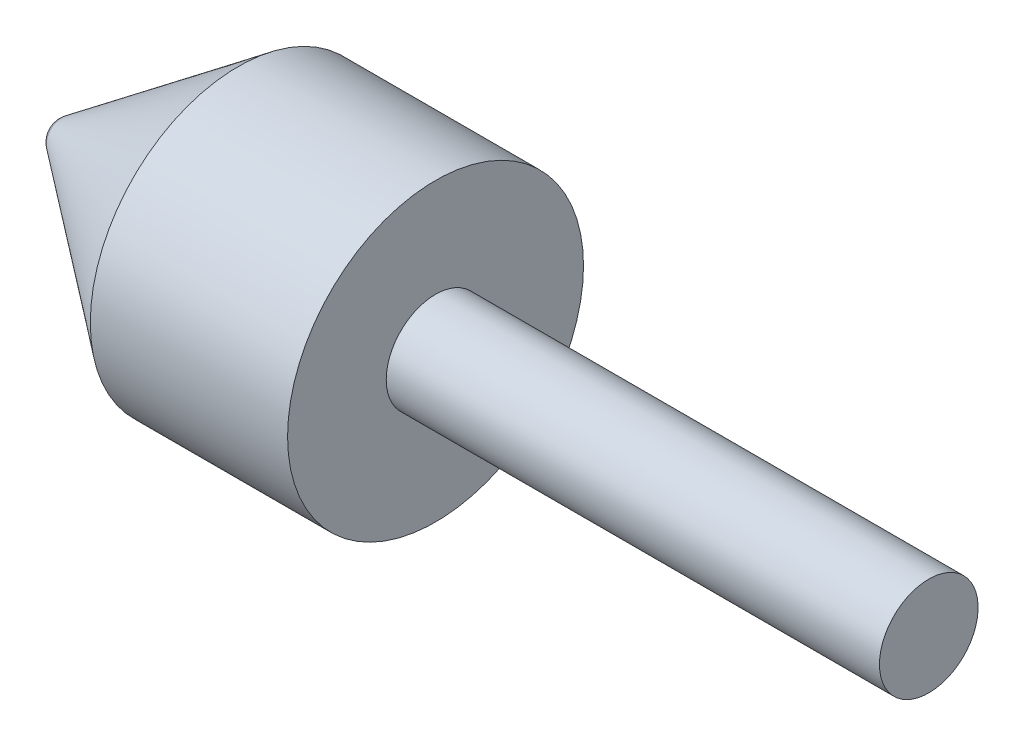
SolidWorks part; units mm, degrees
ref_plane "Plan de face" through (0, 0, 0) normal (0, 0, 1) x (1, 0, 0)
ref_plane "Plan de dessus" through (0, 0, 0) normal (0, 1, 0) x (1, 0, 0)
ref_plane "Plan de droite" through (0, 0, 0) normal (1, 0, 0) x (0, 0, -1)
sketch "Sketch1" plane through (0, 0, 0) normal (0, 0, 1) x (1, 0, 0)
  line L0 (0, 0) -> (0, 0.5)
  line L1 (0, 0.5) -> (-5, 0.5)
  line L2 (-5, 0.5) -> (-5, 1.5)
  line L3 (-5, 1.5) -> (-7, 1.5)
  line L4 (-8.8667, 0) -> (0, 0)
  line L5 (-8.7867, 0.16) -> (-7, 1.5)
  arc A0 (-8.8667, 0) -> (-8.7867, 0.16) centre (-8.6667, 0) cw
  dimension "D6" = 0.2
  dimension "D1" = 0.5
  dimension "D2" = 5
  dimension "D3" = 1
  dimension "D4" = 2
  dimension "D5" = 8.8667
  dimension "D7" = 2.2333
revolve "Revolve1" add sketch "Sketch1" angle 360 about L4
sketch "Pour le placement du ressort" plane through (-5, 0, 0) normal (1, 0, 0) x (0, 0, -1)
  circle A0 centre (0, 0) radius 1 construction
  dimension "D1" = 1
